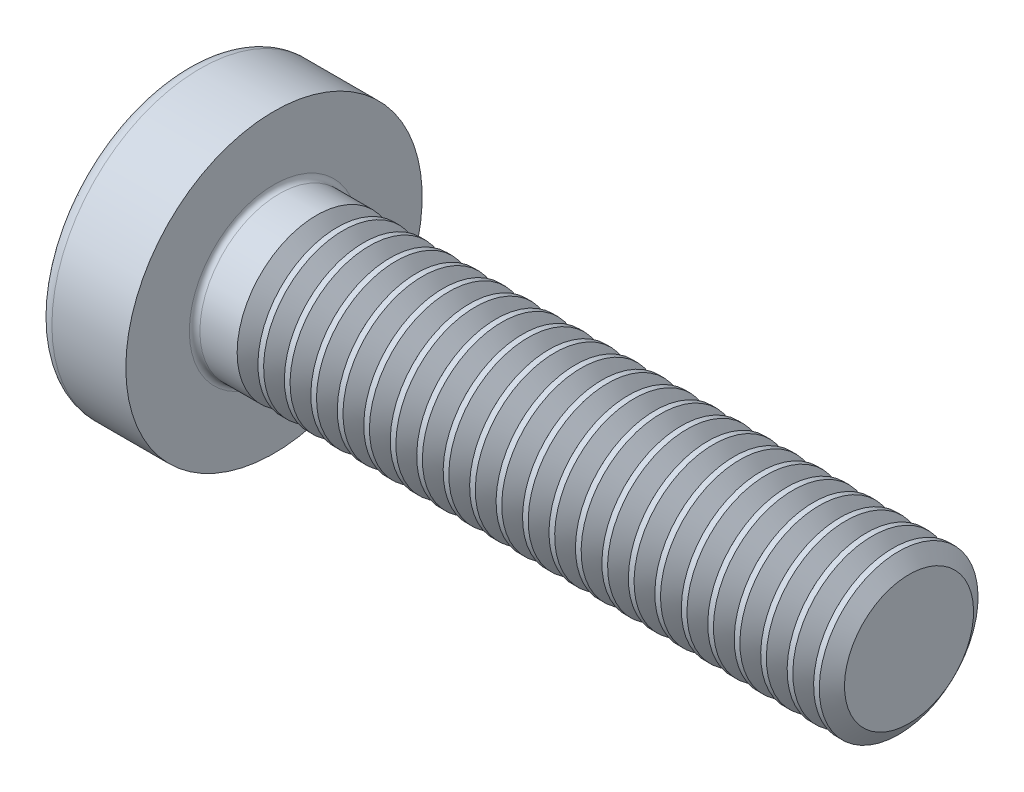
SolidWorks part; units mm, degrees
ref_plane "Plane1" through (0, 0, 0) normal (0, 0, 1) x (1, 0, 0)
ref_plane "Plane2" through (0, 0, 0) normal (0, 1, 0) x (1, 0, 0)
ref_plane "Plane3" through (0, 0, 0) normal (1, 0, 0) x (0, 0, -1)
sketch "BodySke" plane through (0, 0, 0) normal (0, 0, 1) x (1, 0, 0)
  line L0 (2.4, 1.5) -> (2.4, 2.8)
  line L1 (2.65, 6.35) -> (2.65, -3.175) construction
  line L2 (-25.4, 0) -> (127, 0) construction
  line L3 (14.4, 0) -> (0, 0)
  line L4 (2.4, 1.5) -> (14.4, 1.5)
  line L5 (14.4, 1.5) -> (14.4, 0)
  line L6 (1.0035, 2.8) -> (2.4, 2.8)
  line L8 (2.4, 6.35) -> (2.4, -3.175) construction
  arc A0 (0.7754, 2.6744) -> (0, 0) centre (5, 0) ccw
  arc A2 (0.7754, 2.6744) -> (1.0035, 2.8) centre (1.0035, 2.53) cw
  dimension "Head_fillet_rad" = 0.27
  dimension "Head_crown_rad" = 5
  dimension "Head_ht" = 2.4
  dimension "Diameter" = 3
  dimension "Length" = 12
  dimension "Head_dia" = 5.6
  dimension "Advance" = 0.5
  dimension "Thread_nom" = 12
revolve "Base-Revolve" add sketch "BodySke"
cosmetic thread "ThreadCosmetic" [suppressed]
fillet "Fillet1" radius 0.1 1 edges at (2.4, 0, 1.5)
sketch "Sketch3" plane through (0, 0, 0) normal (1, 0, 0) x (0, 0, -1)
  line L0 (0.37, -1.4) -> (-0.37, -1.4)
  line L1 (0.37, -1.4) -> (0.37, 1.4)
  line L2 (-0.37, 1.4) -> (0.37, 1.4)
  line L3 (-0.37, 1.4) -> (-0.37, -1.4)
  dimension "D1" = 1.4
  dimension "Cross_dia" = 2.8
  dimension "D2" = 0.37
  dimension "Cross_width" = 0.74
ref_plane "Plane4" through (1.75, 0, 0) normal (1, 0, 0) x (0, 0, -1)
sketch "Sketch4" plane through (1.75, 0, 0) normal (1, 0, 0) x (0, 0, -1)
  line L0 (0.37, -0.5275) -> (-0.37, -0.5275)
  line L1 (0.37, -0.5275) -> (0.37, 0.5275)
  line L2 (-0.37, 0.5275) -> (0.37, 0.5275)
  line L3 (-0.37, 0.5275) -> (-0.37, -0.5275)
  dimension "D1" = 0.74
  dimension "D2" = 1.055
  dimension "D3" = 0.37
  dimension "D4" = 0.5275
loft "Recess" cut profiles "Sketch3", "Sketch4"
pattern_circular "RecPat" count 2 every 90 about axis through (0, 0, 0) along (1, 0, 0) of "Recess"
sketch "RecCorSke" plane through (0, 0, 0) normal (0, 0, 1) x (1, 0, 0)
  line L0 (-3.175, 0) -> (15.875, 0) construction
  line L1 (-25.4, 0) -> (127, 0) construction
  line L2 (0, 0) -> (0, 0.6784)
  line L3 (0, 0.6784) -> (1.75, 0.556)
  line L4 (1.75, 0.556) -> (1.9307, 0)
  line L5 (1.9307, 0) -> (0, 0)
  dimension "Diameter" = 1.112
  dimension "Depth" = 1.75
  dimension "Draft_angle" = 4
  dimension "Bottom_angle" = 18
revolve "RecessCore" cut sketch "RecCorSke" angle 360 about L0
sketch "ThdSchSke" plane through (0, 0, 0) normal (0, 0, 1) x (1, 0, 0)
  line L0 (3.4, -1.2195) -> (3.2036, -1.5)
  line L1 (3.4, -1.2195) -> (3.5964, -1.5)
  line L2 (3.5964, -1.5) -> (3.5964, -1.875)
  line L3 (-3.175, 0) -> (5.1513, 0) construction
  line L5 (3.5964, -1.875) -> (3.2036, -1.875)
  line L6 (3.2036, -1.875) -> (3.2036, -1.5)
  dimension "Thread_minor" = 2.439
  dimension "Diameter" = 3
  dimension "Start" = 3.4
  dimension "SideAngle" = 55
  dimension "VeeAngle" = 70
  dimension "Overcut" = 3.75
revolve "ThreadSchematic" cut sketch "ThdSchSke" angle 360 about L3
pattern_linear "ThdSchPat" count 23 spacing 0.5 along (1, 0, 0) of "ThreadSchematic"
equation "\"D1@Sketch3\" = \"Cross_dia@Sketch3\" / 2"
equation "\"D2@Sketch3\" = \"Cross_width@Sketch3\" / 2"
equation "\"Depth@RecCorSke\" = \"Cross_depth@Plane4\""
equation "\"D1@Sketch4\" = \"Cross_width@Sketch3\""
equation "\"D2@Sketch4\" = \"Cross_dia@Sketch3\" - 2.0 * \"Cross_depth@Plane4\" * tan(26.5  * 0.017453292)"
equation "\"D3@Sketch4\" = \"D1@Sketch4\" / 2"
equation "\"D4@Sketch4\" = \"D2@Sketch4\" / 2"
equation "\"Thread_length@ThreadCosmetic\" = ((sgn( (\"Length@BodySke\" - \"Advance@BodySke\" * 2.0 ) - \"Thread_nom@BodySke\" )-1)*( (\"Length@BodySke\" - \"Advance@BodySke\" * 2.0 ) - \"Thread_nom@BodySke\" ))/-2+ \"Thread_nom@BodySke\""
equation "\"Thread_minor@ThdSchSke\" = \"Thread_minor@ThreadCosmetic\""
equation "\"Diameter@ThdSchSke\" = \"Diameter@BodySke\""
equation "\"Overcut@ThdSchSke\" = \"Diameter@BodySke\" * 1.25"
equation "\"Start@ThdSchSke\" = \"Head_ht@BodySke\" + \"Length@BodySke\" - \"Thread_length@ThreadCosmetic\"  '---Non-countersunk---"
equation "\"Num_threads@ThdSchPat\" = int( \"Thread_length@ThreadCosmetic\" / \"Advance@BodySke\" + 0.999 )  + 1"
equation "\"Advance@ThdSchPat\" = \"Thread_length@ThreadCosmetic\" /  (\"Num_threads@ThdSchPat\" - 1) 'relax it"
